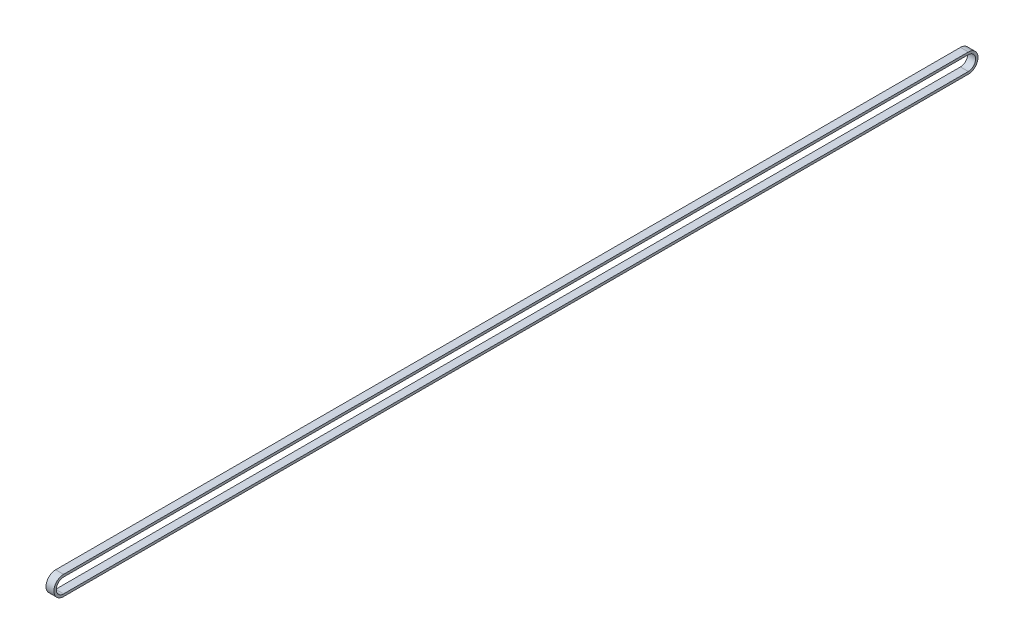
SolidWorks part; units mm, degrees
ref_plane "前视基准面" through (0, 0, 0) normal (0, 0, 1) x (1, 0, 0)
ref_plane "上视基准面" through (0, 0, 0) normal (0, 1, 0) x (1, 0, 0)
ref_plane "右视基准面" through (0, 0, 0) normal (1, 0, 0) x (0, 0, -1)
other "Configuration Table"
sketch "草图1" plane through (0, 0, 0) normal (1, 0, 0) x (0, 0, -1)
  line L0 (0, 21.34) -> (1141, 21.34)
  line L1 (0, 0) -> (1141, 0)
  line L3 (0, 18.34) -> (1141, 18.34)
  line L5 (0, -3) -> (1141, -3)
  arc A0 (0, 0) -> (0, 18.34) centre (0, 9.17) cw
  arc A1 (1141, 0) -> (1141, 18.34) centre (1141, 9.17) ccw
  arc A2 (1141, -3) -> (1141, 21.34) centre (1141, 9.17) ccw
  arc A3 (0, -3) -> (0, 21.34) centre (0, 9.17) cw
  dimension "D1" = 1141
  dimension "D2" = 18.34
  dimension "D3" = 3
extrude "凸台-拉伸1" add sketch "草图1" along normal blind 10
